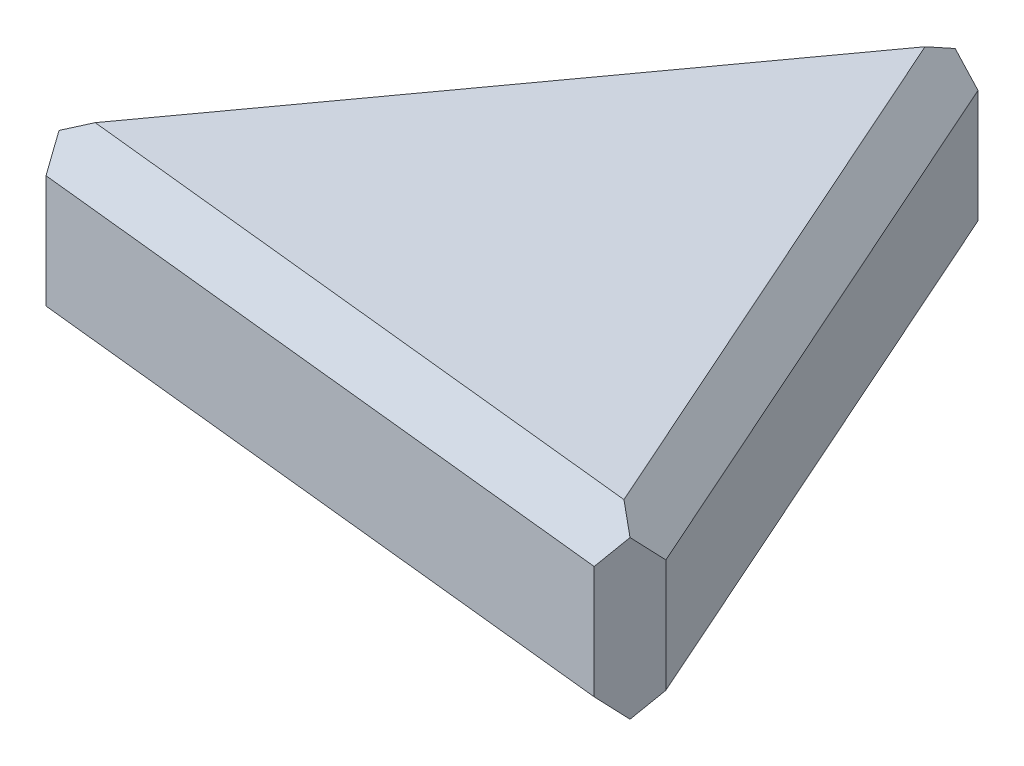
SolidWorks part; units mm, degrees
material "Chêne"
ref_plane "Plan de face" through (0, 0, 0) normal (0, 0, 1) x (1, 0, 0)
ref_plane "Plan de dessus" through (0, 0, 0) normal (0, 1, 0) x (1, 0, 0)
ref_plane "Plan de droite" through (0, 0, 0) normal (1, 0, 0) x (0, 0, -1)
sketch "Esquisse1" plane through (0, 0, 0) normal (0, 1, 0) x (1, 0, 0)
  line L1 (43.2536, -35.2378) -> (-13.6935, 92.6568)
  line L2 (-13.6935, 92.6568) -> (-95.9799, -20.6081)
  line L3 (-95.9799, -20.6081) -> (43.2536, -35.2378)
  circle A0 centre (-22.1399, 12.2703) radius 40.4145 construction
  dimension "D1" = 140
extrude "Boss.-Extru.1" add sketch "Esquisse1" along normal blind 36
chamfer "Chanfrein1" distance 7 angle 45 6 edges at (14.7801, 0, -28.7095) (-26.3632, 0, 27.9229) (-54.8367, 0, -36.0244) (-26.3632, 36, 27.9229) (14.7801, 36, -28.7095) (-54.8367, 36, -36.0244)
chamfer "Chanfrein2" distance 10 distance2 10 3 edges at (43.2536, 18, 35.2378) (-13.6935, 18, -92.6568) (-95.9799, 18, 20.6081)
